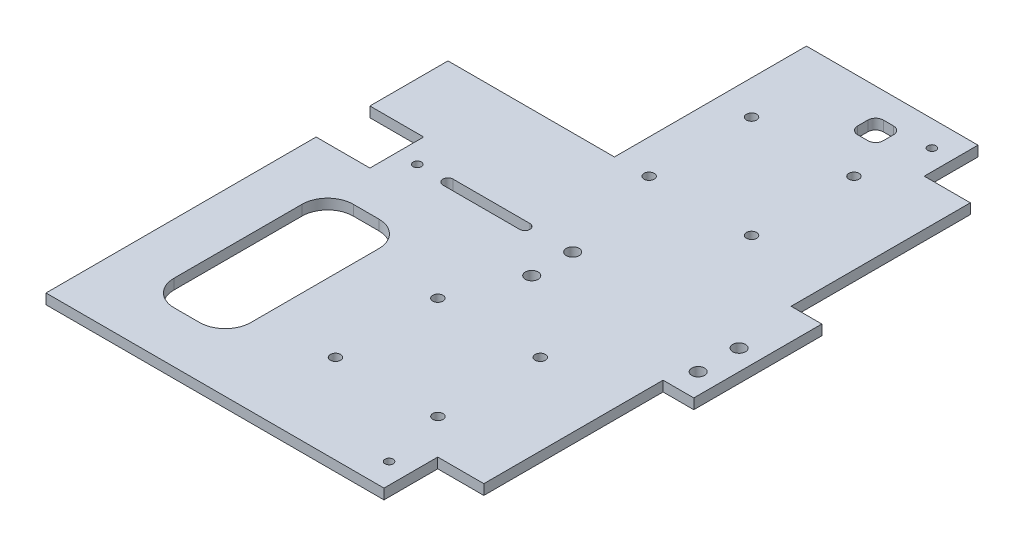
SolidWorks part; units mm, degrees
ref_plane "Front Plane" through (0, 0, 0) normal (0, 0, 1) x (1, 0, 0)
ref_plane "Top Plane" through (0, 0, 0) normal (0, 1, 0) x (1, 0, 0)
ref_plane "Right Plane" through (0, 0, 0) normal (1, 0, 0) x (0, 0, -1)
sketch "Sketch1" plane through (0, 0, 0) normal (0, 1, 0) x (1, 0, 0)
  line L1 (-77, 120) -> (85, 120)
  line L2 (-77, 120) -> (-77, -112)
  line L3 (-77, -112) -> (85, -112)
  line L4 (85, 120) -> (85, -112)
  dimension "D1" = 232
  dimension "D2" = 120
  dimension "D3" = 162
  dimension "D4" = 85
extrude "Boss-Extrude1" add sketch "Sketch1" along normal blind 4
sketch "Sketch2" plane through (0, 0, 0) normal (0, -1, 0) x (1, 0, 0)
  line L0 (-77, -120) -> (-77, 112) construction
  line L1 (-56, 10.5) -> (-77, 10.5)
  line L2 (-56, 10.5) -> (-56, -10.5)
  line L3 (-56, -10.5) -> (-77, -10.5)
  line L4 (-77, 10.5) -> (-77, -10.5)
  line L5 (-56, 10.5) -> (-77, -10.5) construction
  line L6 (-56, -10.5) -> (-77, 10.5) construction
  line L7 (85, 112) -> (85, -120) construction
  line L8 (64, 112) -> (85, 112)
  line L9 (64, 112) -> (64, 91)
  line L10 (64, 91) -> (85, 91)
  line L11 (85, 112) -> (85, 91)
  line L12 (64, 112) -> (85, 91) construction
  line L13 (64, 91) -> (85, 112) construction
  line L14 (64, -99) -> (85, -99)
  line L15 (64, -99) -> (64, -120)
  line L16 (64, -120) -> (85, -120)
  line L17 (85, -99) -> (85, -120)
  line L18 (64, -99) -> (85, -120) construction
  line L19 (64, -120) -> (85, -99) construction
  line L20 (85, -120) -> (-77, -120) construction
  line L21 (-77, 112) -> (85, 112) construction
  point P0 (-66.5, 0)
  point P7 (74.5, 101.5)
  point P13 (74.5, -109.5)
  dimension "D1" = 21
  dimension "D2" = 21
  dimension "D3" = 21
extrude "Cut-Extrude1" [suppressed] cut sketch "Sketch2" against normal through all
sketch "Sketch3" plane through (0, 0, 0) normal (0, -1, 0) x (1, 0, 0)
  line L0 (85, 112) -> (85, -120) construction
  line L1 (81, 112) -> (85, 112)
  line L2 (81, 112) -> (81, -120)
  line L3 (81, -120) -> (85, -120)
  line L4 (85, 112) -> (85, -120)
  line L5 (81, 112) -> (85, -120) construction
  line L6 (81, -120) -> (85, 112) construction
  line L7 (85, -120) -> (-77, -120) construction
  line L8 (-77, 112) -> (85, 112) construction
  point P0 (83, -4)
  dimension "D1" = 4
extrude "Cut-Extrude2" [suppressed] cut sketch "Sketch3" against normal through all
sketch "Sketch4" plane through (0, 4, 0) normal (0, 1, 0) x (1, 0, 0)
  line L0 (85, -112) -> (85, 120) construction
  line L1 (85, 120) -> (55, 120)
  line L2 (85, 120) -> (85, 99)
  line L3 (85, 99) -> (55, 99)
  line L4 (55, 120) -> (55, 99)
  line L5 (85, 120) -> (55, 99) construction
  line L6 (85, 99) -> (55, 120) construction
  line L7 (85, 120) -> (-77, 120) construction
  line L8 (-77, 120) -> (-77, -112) construction
  line L9 (-56, 14.5) -> (-77, 14.5)
  line L10 (-56, 14.5) -> (-56, -6.5)
  line L11 (-56, -6.5) -> (-77, -6.5)
  line L12 (-77, 14.5) -> (-77, -6.5)
  line L13 (-56, 14.5) -> (-77, -6.5) construction
  line L14 (-56, -6.5) -> (-77, 14.5) construction
  line L15 (-77, -112) -> (85, -112) construction
  line L16 (85, -91) -> (55, -91)
  line L17 (85, -91) -> (85, -112)
  line L18 (85, -112) -> (55, -112)
  line L19 (55, -91) -> (55, -112)
  line L20 (85, -91) -> (55, -112) construction
  line L21 (85, -112) -> (55, -91) construction
  point P0 (70, 109.5)
  point P9 (-66.5, 4)
  point P17 (-77, 4)
  point P18 (-77, 4)
  point P20 (70, -101.5)
  dimension "D1" = 30
  dimension "D2" = 21
  dimension "D3" = 21
  dimension "D4" = 21
  dimension "D5" = 21
extrude "Cut-Extrude3" cut sketch "Sketch4" against normal through all
sketch "Sketch5" plane through (0, 0, 0) normal (0, -1, 0) x (1, 0, 0)
  circle A0 centre (-48, -4) radius 1.6
  circle A1 centre (47, -110) radius 1.6
  circle A2 centre (47, 102) radius 1.6
  circle A3 centre (41.3, 37.25) radius 2
  circle A4 centre (41.3, 77.25) radius 2
  circle A5 centre (1.3, 37.25) radius 2
  circle A6 centre (1.3, 77.25) radius 2
  circle A7 centre (41.3, -45.25) radius 2
  circle A8 centre (1.3, -45.25) radius 2
  circle A9 centre (1.3, -85.25) radius 2
  circle A10 centre (41.3, -85.25) radius 2
  dimension "D1" = 3.2
  dimension "D2" = 3.2
  dimension "D3" = 3.2
  dimension "D4" = 4
  dimension "D5" = 4
extrude "Cut-Extrude4" cut sketch "Sketch5" against normal through all
sketch "Sketch6" plane through (0, 0, 0) normal (0, -1, 0) x (1, 0, 0)
  line L0 (-77, -120) -> (-77, -14.5) construction
  line L1 (55, -120) -> (-77, -120) construction
  line L2 (-56, -4) -> (85, -4) construction
  line L3 (-56, 6.5) -> (-56, -14.5) construction
  line L4 (85, 91) -> (85, -99) construction
  circle A0 centre (-27, -49) radius 2
  circle A1 centre (25, -49) radius 2
  circle A2 centre (-27, -85) radius 2
  circle A3 centre (25, -85) radius 2
  circle A4 centre (25, 77) radius 2
  circle A5 centre (-27, 77) radius 2
  circle A6 centre (25, 41) radius 2
  circle A7 centre (-27, 41) radius 2
  dimension "D1" = 4
  dimension "D2" = 52
  dimension "D3" = 36
  dimension "D4" = 50
  dimension "D5" = 35
extrude "Cut-Extrude5" [suppressed] cut sketch "Sketch6" against normal through all
sketch "Sketch7" plane through (0, 0, 0) normal (0, -1, 0) x (1, 0, 0)
  line L0 (55, -120) -> (-77, -120) construction
  line L1 (-77, -45) -> (-12, -45)
  line L2 (-77, -45) -> (-77, -120)
  line L3 (-77, -120) -> (-12, -120)
  line L4 (-12, -45) -> (-12, -120)
  line L5 (-77, -120) -> (-77, -14.5) construction
  dimension "D1" = 75
  dimension "D2" = 65
extrude "Cut-Extrude6" cut sketch "Sketch7" against normal through all
sketch "Sketch8" plane through (0, 0, 0) normal (0, -1, 0) x (1, 0, 0)
  line L0 (-77, 112) -> (55, 112) construction
  line L1 (-47, 92) -> (-37, 92)
  line L2 (-57, 82) -> (-57, 32)
  line L3 (-47, 22) -> (-37, 22)
  line L4 (-27, 82) -> (-27, 32)
  line L5 (-77, 6.5) -> (-77, 112) construction
  arc A0 (-57, 32) -> (-47, 22) centre (-47, 32) ccw
  arc A1 (-37, 22) -> (-27, 32) centre (-37, 32) ccw
  arc A2 (-37, 92) -> (-27, 82) centre (-37, 82) cw
  arc A3 (-47, 92) -> (-57, 82) centre (-47, 82) ccw
  point P10 (-57, 22)
  point P13 (-27, 22)
  point P18 (-57, 92)
  dimension "D5" = 10
  dimension "D1" = 20
  dimension "D2" = 70
  dimension "D3" = 30
  dimension "D4" = 20
extrude "Cut-Extrude7" cut sketch "Sketch8" against normal through all
sketch "Sketch9" plane through (0, 4, 0) normal (0, 1, 0) x (1, 0, 0)
  line L0 (55, 120) -> (-12, 120) construction
  line L1 (28, 100) -> (32, 100)
  line L2 (25, 103) -> (25, 107)
  line L3 (28, 110) -> (32, 110)
  line L4 (35, 103) -> (35, 107)
  arc A0 (25, 107) -> (28, 110) centre (28, 107) cw
  arc A1 (28, 100) -> (25, 103) centre (28, 103) cw
  arc A2 (32, 100) -> (35, 103) centre (32, 103) ccw
  arc A3 (32, 110) -> (35, 107) centre (32, 107) cw
  point P4 (30, 110)
  point P12 (25, 100)
  point P15 (35, 100)
  point P18 (35, 110)
  dimension "D5" = 3
  dimension "D1" = 10
  dimension "D2" = 10
  dimension "D3" = 10
  dimension "D4" = 20
extrude "Cut-Extrude8" cut sketch "Sketch9" against normal through all
sketch "Sketch10" plane through (0, 4, 0) normal (0, 1, 0) x (1, 0, 0)
  circle A0 centre (12, -11.2919) radius 2.5
  circle A1 centre (12, 4.7081) radius 2.5
  circle A2 centre (77, 4.7081) radius 2.5
  circle A3 centre (77, -11.2919) radius 2.5
extrude "Cut-Extrude9" cut sketch "Sketch10" against normal through all
sketch "Sketch11" plane through (0, 4, 0) normal (0, 1, 0) x (1, 0, 0)
  line L0 (-36, 4) -> (-6, 4) construction
  line L1 (-36, 6) -> (-6, 6)
  line L2 (-36, 2) -> (-6, 2)
  line L3 (-56, -6.5) -> (-56, 14.5) construction
  arc A0 (-36, 6) -> (-36, 2) centre (-36, 4) ccw
  arc A1 (-6, 2) -> (-6, 6) centre (-6, 4) ccw
  point P2 (-21, 4)
  point P11 (-56, 4)
  dimension "D1" = 2
  dimension "D2" = 30
  dimension "D3" = 20
extrude "Cut-Extrude10" cut sketch "Sketch11" against normal blind 4
sketch "Sketch12" plane through (0, 4, 0) normal (0, 1, 0) x (1, 0, 0)
  line L1 (85, 99) -> (73, 99)
  line L2 (85, 99) -> (85, 29)
  line L3 (85, 29) -> (73, 29)
  line L4 (73, 99) -> (73, 29)
  line L5 (85, -91) -> (73, -91)
  line L6 (85, -91) -> (85, -21)
  line L7 (85, -21) -> (73, -21)
  line L8 (73, -91) -> (73, -21)
  dimension "D1" = 70
  dimension "D2" = 12
extrude "Cut-Extrude11" cut sketch "Sketch12" against normal blind 4
